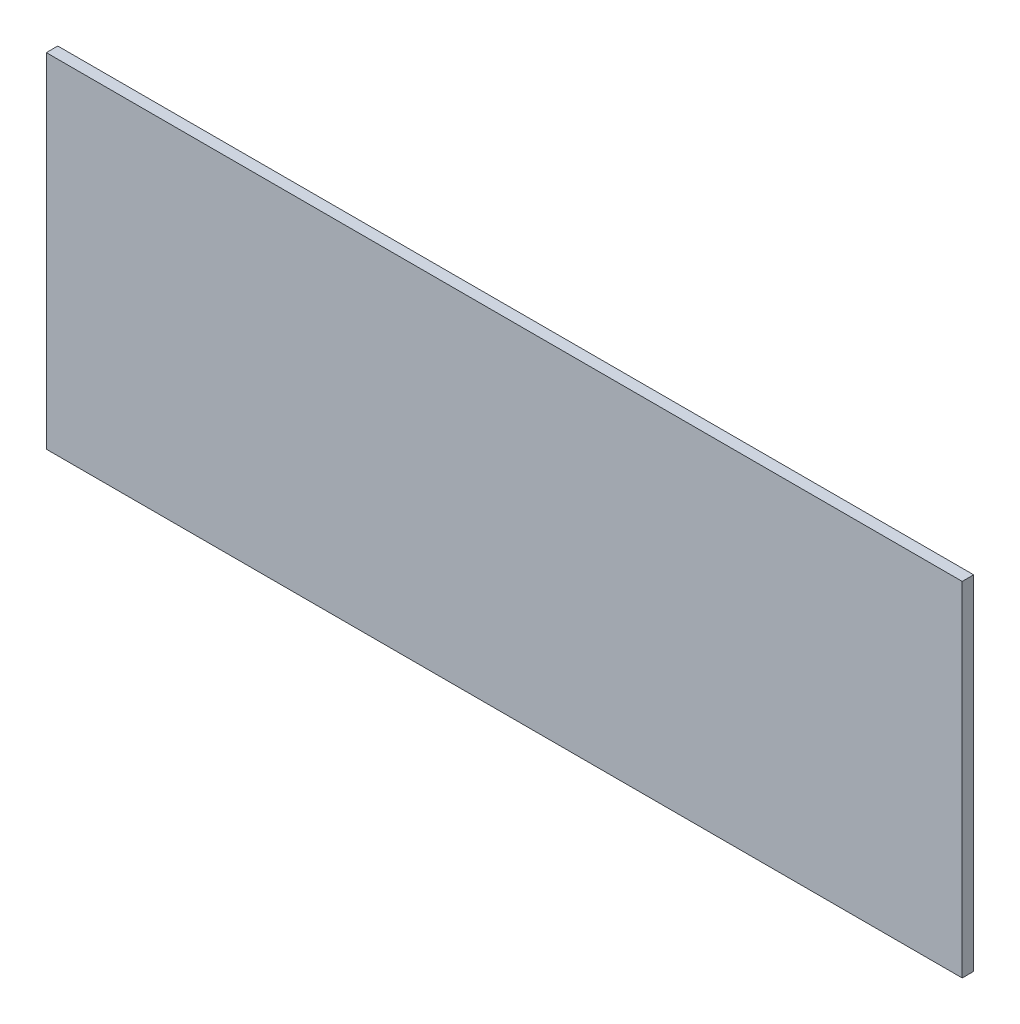
SolidWorks part; units mm, degrees
ref_plane "Front Plane" through (0, 0, 0) normal (0, 0, 1) x (1, 0, 0)
ref_plane "Top Plane" through (0, 0, 0) normal (0, 1, 0) x (1, 0, 0)
ref_plane "Right Plane" through (0, 0, 0) normal (1, 0, 0) x (0, 0, -1)
sketch "Sketch1" plane through (0, 0, 0) normal (0, 0, 1) x (1, 0, 0)
  line L1 (-40, -15) -> (40, -15)
  line L2 (-40, -15) -> (-40, 15)
  line L3 (-40, 15) -> (40, 15)
  line L4 (40, -15) -> (40, 15)
  line L5 (-40, -15) -> (40, 15) construction
  line L6 (-40, 15) -> (40, -15) construction
  point P0 (0, 0)
  dimension "D1" = 80
  dimension "D2" = 30
extrude "Boss-Extrude1" add sketch "Sketch1" along normal blind 1
